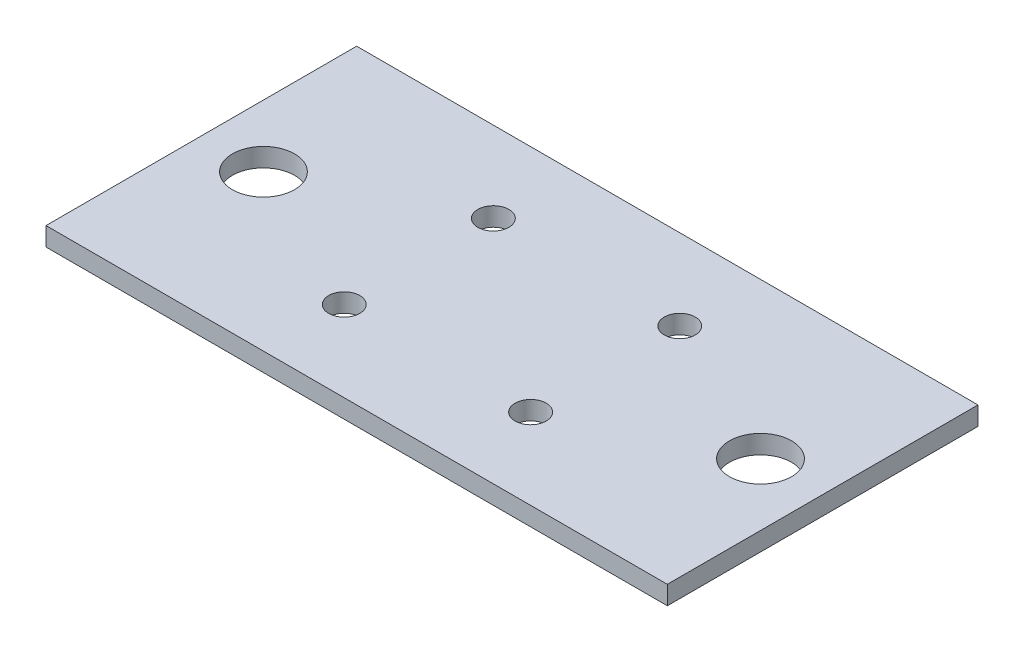
SolidWorks part; units mm, degrees
ref_plane "Front Plane" through (0, 0, 0) normal (0, 0, 1) x (1, 0, 0)
ref_plane "Top Plane" through (0, 0, 0) normal (0, 1, 0) x (1, 0, 0)
ref_plane "Right Plane" through (0, 0, 0) normal (1, 0, 0) x (0, 0, -1)
sketch "Sketch2" plane through (0, 0, 0) normal (0, 1, 0) x (1, 0, 0)
  line L1 (-50, 25) -> (50, 25)
  line L2 (-50, 25) -> (-50, -25)
  line L3 (-50, -25) -> (50, -25)
  line L4 (50, 25) -> (50, -25)
  line L5 (-50, 25) -> (50, -25) construction
  line L6 (-50, -25) -> (50, 25) construction
  point P0 (0, 0)
extrude "Boss-Extrude2" add sketch "Sketch2" along normal blind 3
sketch "Sketch5" plane through (0, 3, 0) normal (0, 1, 0) x (1, 0, 0)
  line L0 (-40, 0) -> (40, 0) construction
  line L1 (-15, 12) -> (15, 12) construction
  line L2 (15, 12) -> (15, -12) construction
  line L3 (-15, -12) -> (15, -12) construction
  circle A0 centre (-40, 0) radius 5
  circle A1 centre (40, 0) radius 5
  circle A2 centre (-15, 12) radius 2.5
  circle A3 centre (-15, -12) radius 2.5
  circle A4 centre (15, 12) radius 2.5
  circle A5 centre (15, -12) radius 2.5
extrude "Cut-Extrude1" cut sketch "Sketch5" against normal blind 3
